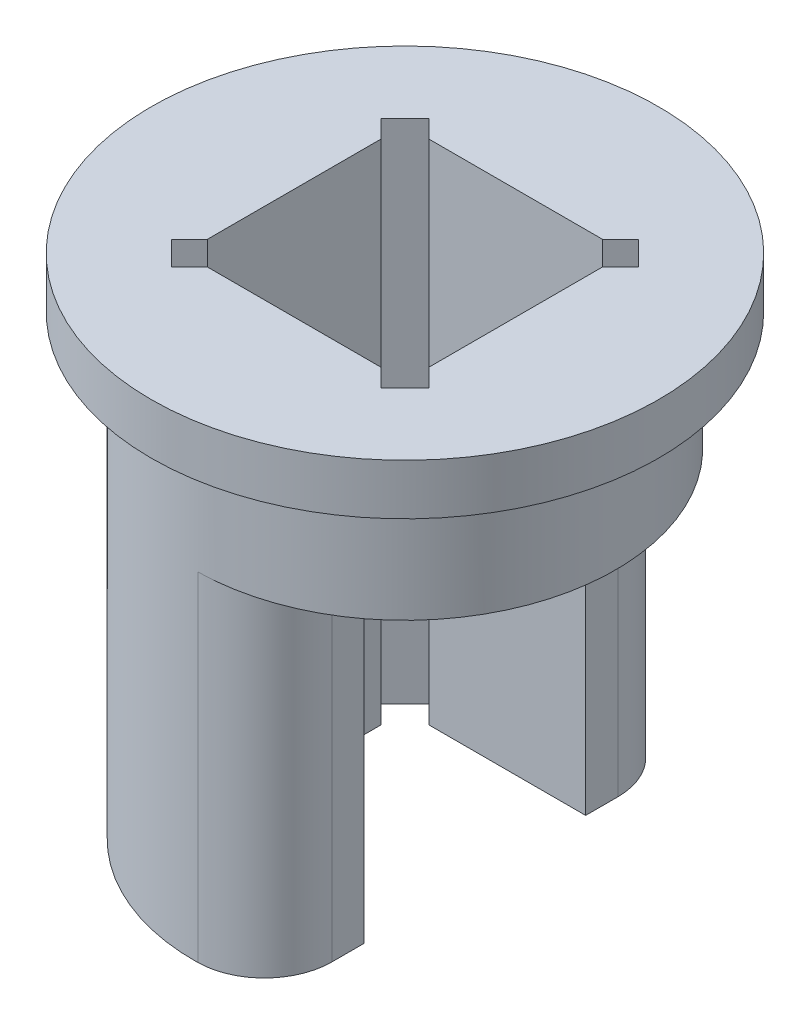
SolidWorks part; units mm, degrees
ref_plane "Front Plane" through (0, 0, 0) normal (0, 0, 1) x (1, 0, 0)
ref_plane "Top Plane" through (0, 0, 0) normal (0, 1, 0) x (1, 0, 0)
ref_plane "Right Plane" through (0, 0, 0) normal (1, 0, 0) x (0, 0, -1)
sketch "Sketch1" plane through (0, 0, 0) normal (0, 1, 0) x (1, 0, 0)
  line L0 (7.6107, 6.1964) -> (-6.1964, -7.6107)
  line L1 (-6.55, -6.55) -> (6.55, -6.55)
  line L2 (-6.55, -6.55) -> (-6.55, 6.55)
  line L3 (-6.55, 6.55) -> (6.55, 6.55)
  line L4 (6.55, -6.55) -> (6.55, 6.55)
  line L5 (-6.55, -6.55) -> (6.55, 6.55) construction
  line L6 (-6.55, 6.55) -> (6.55, -6.55) construction
  line L7 (7.6107, 6.1964) -> (6.1964, 7.6107)
  line L8 (-6.1964, -7.6107) -> (-7.6107, -6.1964)
  line L9 (6.1964, 7.6107) -> (-7.6107, -6.1964)
  line L10 (7.6107, 6.1964) -> (-7.6107, -6.1964) construction
  line L11 (-6.1964, -7.6107) -> (6.1964, 7.6107) construction
  line L12 (-7.6107, 6.1964) -> (6.1964, -7.6107)
  line L13 (-7.6107, 6.1964) -> (-6.1964, 7.6107)
  line L14 (6.1964, -7.6107) -> (7.6107, -6.1964)
  line L15 (-6.1964, 7.6107) -> (7.6107, -6.1964)
  line L16 (-7.6107, 6.1964) -> (7.6107, -6.1964) construction
  line L17 (6.1964, -7.6107) -> (-6.1964, 7.6107) construction
  circle A0 centre (0, 0) radius 12.45
  dimension "D1" = 24.9
  dimension "D2" = 13.1
  dimension "D3" = 13.1
  dimension "D4" = 1
  dimension "D5" = 0.5
extrude "Boss-Extrude3" add sketch "Sketch1" along normal blind 30 contours A0 L13 L15 L3 L9 L7 L0 L4 L14 L12 L1 L8 L2
sketch "Sketch4" plane through (0, 30, 0) normal (0, 1, 0) x (1, 0, 0)
  circle A0 centre (0, 0) radius 12.45 construction
  circle A1 centre (0, 0) radius 12.45
  circle A2 centre (0, 0) radius 15
  dimension "D1" = 30
extrude "Boss-Extrude4" add sketch "Sketch4" against normal blind 3
sketch "Sketch5" plane through (0, 0, 0) normal (0, -1, 0) x (1, 0, 0)
  line L0 (4.1358, -11.743) -> (4.1358, 11.743)
  circle A0 centre (0, 0) radius 12.45 construction
  arc A1 (4.1358, -11.743) -> (4.1358, 11.743) centre (0, 0) ccw
  point P4 (4.4381, 11.6321)
  point P5 (4.6365, -11.5544)
  dimension "D1" = 1
extrude "Cut-Extrude1" cut sketch "Sketch5" against normal blind 20
fillet "Fillet1" radius 4 2 edges at (4.1358, 10, -11.743) (4.1358, 10, 11.743)
